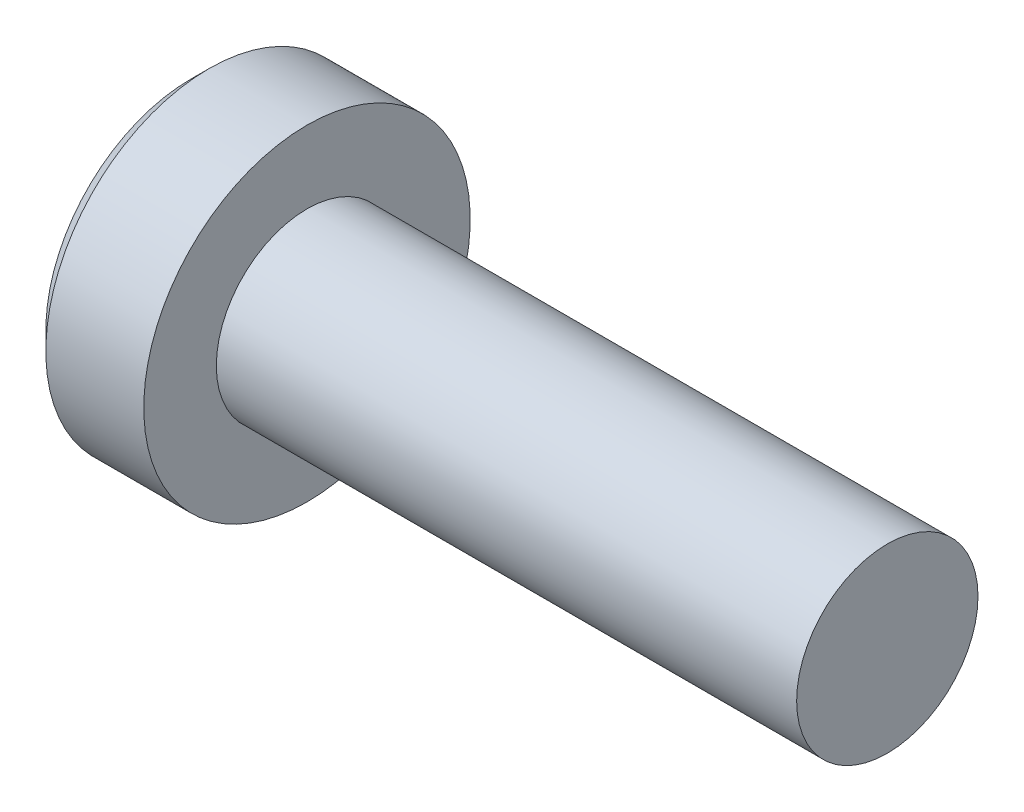
SolidWorks part; units mm, degrees
ref_plane "Front Plane" through (0, 0, 0) normal (0, 0, 1) x (1, 0, 0)
ref_plane "Top Plane" through (0, 0, 0) normal (0, 1, 0) x (1, 0, 0)
ref_plane "Right Plane" through (0, 0, 0) normal (1, 0, 0) x (0, 0, -1)
sketch "Sketch1" plane through (0, 0, 0) normal (0, 0, 1) x (1, 0, 0)
  line L0 (-1.6, 0) -> (8, 0) construction
  line L1 (8, 0) -> (8, 1.25)
  line L2 (8, 1.25) -> (0, 1.25)
  line L3 (0, 1.25) -> (0, 2.25)
  line L4 (0, 2.25) -> (-1.6, 2.25)
  line L5 (-1.6, 2.25) -> (-1.6, 0)
  line L6 (-1.6, 0) -> (8, 0)
  dimension "MSM_71" = 2.5
  dimension "MSM_72" = 4.5
  dimension "MSM_73" = 8
  dimension "MSM_74" = 1.6
revolve "Revolve1" add sketch "Sketch1" angle 360 about L0
cosmetic thread "Thread8" parameters "ATD"=2.013
sketch "Sketch2" plane through (-1.6, 0, 0) normal (-1, 0, 0) x (0, 0, 1)
  line L1 (0, 1.1547) -> (-1, 0.5774)
  line L2 (-1, 0.5774) -> (-1, -0.5774)
  line L3 (-1, -0.5774) -> (0, -1.1547)
  line L4 (0, -1.1547) -> (1, -0.5774)
  line L5 (1, -0.5774) -> (1, 0.5774)
  line L6 (1, 0.5774) -> (0, 1.1547)
  circle A0 centre (0, 0) radius 1 construction
  dimension "MSM_75" = 2
extrude "Cut-Extrude1" cut sketch "Sketch2" against normal blind 1.1
sketch "Sketch3" plane through (0, 0, 0) normal (0, 0, 1) x (1, 0, 0)
  line L0 (-0.5, 0) -> (0.0774, 0) construction
  line L1 (-0.5, -0.5774) -> (-0.5, 0.5774) construction
  line L2 (0.0774, 0) -> (-0.5, 1)
  line L3 (-0.5, 0.5774) -> (-0.5, 1.1547) construction
  line L4 (-0.5, 1) -> (-0.5, 0)
  line L5 (-0.5, 0) -> (0.0774, 0)
  dimension "FIX_2" = 30
  dimension "FIX_3" = 2
revolve "Cut-Revolve1" cut sketch "Sketch3" angle 360 about L0
chamfer "Chamfer1" distance 0.25 1 edges at (-1.6, -2.25, 0)
equation "\"FIX_5@Chamfer1\" = \"MSM_71@Sketch1\" / 10"
equation "\"FIX_3@Sketch3\" = \"MSM_75@Sketch2\""
